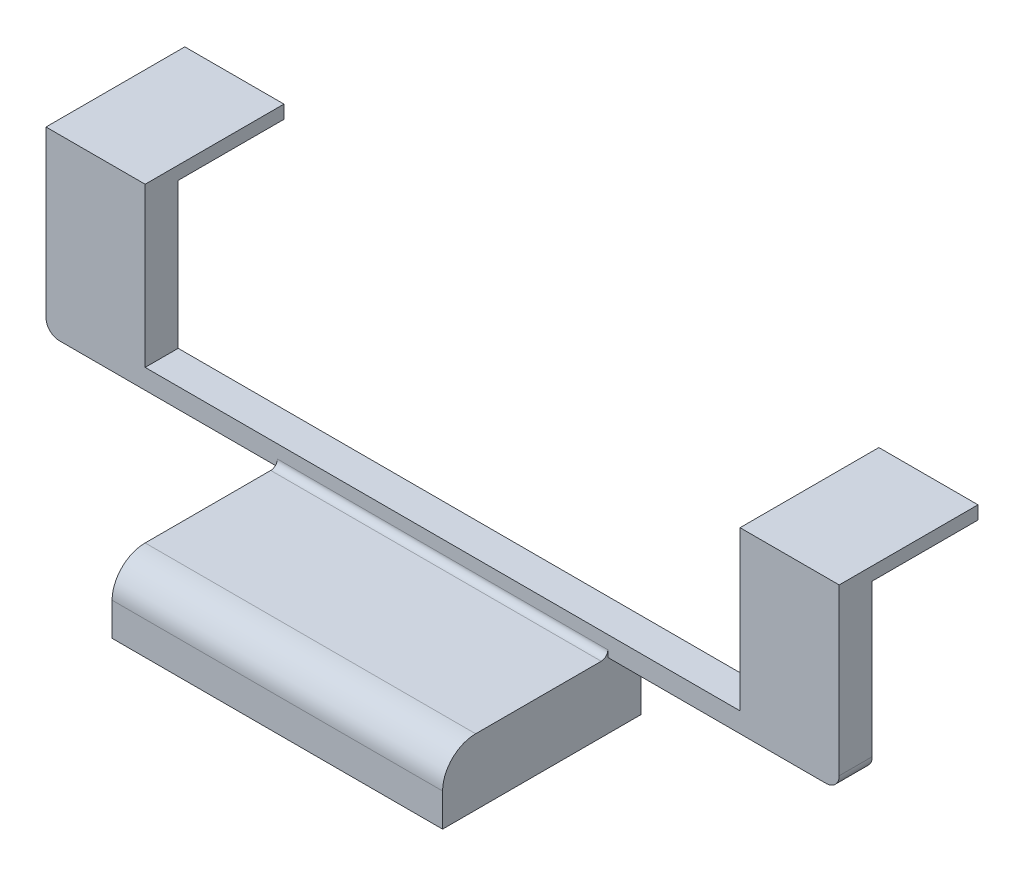
SolidWorks part; units mm, degrees
ref_plane "前视基准面" through (0, 0, 0) normal (0, 0, 1) x (1, 0, 0)
ref_plane "上视基准面" through (0, 0, 0) normal (0, 1, 0) x (1, 0, 0)
ref_plane "右视基准面" through (0, 0, 0) normal (1, 0, 0) x (0, 0, -1)
sketch "草图1" plane through (0, 0, 0) normal (0, 1, 0) x (1, 0, 0)
  line L0 (-55.774, -26.4776) -> (64.226, -26.4776)
  line L1 (64.226, -26.4776) -> (64.226, -31.4776)
  line L2 (64.226, -31.4776) -> (-55.774, -31.4776)
  line L3 (-55.774, -31.4776) -> (-55.774, -26.4776)
extrude "凸台-拉伸1" add sketch "草图1" along normal blind 3
sketch "草图2" plane through (0, 3, 0) normal (0, 1, 0) x (1, 0, 0)
  line L0 (-55.774, -26.4776) -> (-40.774, -26.4776)
  line L1 (64.226, -26.4776) -> (-55.774, -26.4776) construction
  line L2 (-40.774, -26.4776) -> (-40.774, -31.4776)
  line L3 (-55.774, -31.4776) -> (64.226, -31.4776) construction
  line L4 (-40.774, -31.4776) -> (-55.774, -31.4776)
  line L5 (-55.774, -31.4776) -> (-55.774, -26.4776)
  line L6 (64.226, -26.4776) -> (49.226, -26.4776)
  line L7 (49.226, -26.4776) -> (49.226, -31.4776)
  line L8 (49.226, -31.4776) -> (64.226, -31.4776)
  line L9 (64.226, -31.4776) -> (64.226, -26.4776)
extrude "凸台-拉伸2" add sketch "草图2" along normal blind 24
sketch "草图3" plane through (0, 0, 0) normal (0, -1, 0) x (1, 0, 0)
  line L0 (-20.774, 56.4776) -> (29.226, 56.4776)
  line L1 (29.226, 56.4776) -> (29.226, 26.4776)
  line L2 (29.226, 26.4776) -> (-20.774, 26.4776)
  line L3 (-20.774, 26.4776) -> (-20.774, 56.4776)
  line L5 (64.226, 26.4776) -> (-55.774, 26.4776) construction
  point P8 (4.226, 26.4776)
  point P11 (4.226, 26.4776)
extrude "凸台-拉伸3" add sketch "草图3" along normal blind 10
fillet "圆角6" radius 1 1 edges at (4.226, 0, 31.4776)
fillet "圆角7" radius 5 1 edges at (4.226, 0, 56.4776)
fillet "圆角9" radius 2 1 edges at (64.226, 0, 28.9776)
fillet "圆角10" radius 2 1 edges at (-55.774, 0, 28.9776)
sketch "草图4" plane through (0, -10, 0) normal (0, -1, 0) x (1, 0, 0)
  line L0 (29.226, 56.4776) -> (-20.774, 56.4776) construction
  line L1 (29.226, 26.4776) -> (29.226, 56.4776) construction
  arc A0 (-4.0934, 38.0444) -> (12.5455, 38.0444) centre (4.226, 41.4776) ccw
  arc A1 (12.5455, 38.0444) -> (12.5455, 44.9108) centre (13.226, 41.4776) ccw
  arc A2 (-4.0934, 44.9108) -> (-4.0934, 38.0444) centre (-4.774, 41.4776) ccw
  arc A3 (12.5455, 44.9108) -> (-4.0934, 44.9108) centre (4.226, 41.4776) ccw
  point P4 (4.226, 56.4776)
  point P8 (29.226, 41.4776)
extrude "切除-拉伸1" cut sketch "草图4" against normal blind 8
sketch "草图5" plane through (0, 0, 26.4776) normal (0, 0, -1) x (-1, 0, 0)
  line L0 (-64.226, 25) -> (-49.226, 25)
  line L1 (-49.226, 25) -> (-49.226, 27)
  line L2 (-49.226, 27) -> (-49.226, 3) construction
  line L3 (-49.226, 27) -> (-64.226, 27)
  line L4 (-64.226, 27) -> (-64.226, 2) construction
  line L5 (-64.226, 27) -> (-64.226, 25)
  line L6 (40.774, 25) -> (40.774, 27)
  line L7 (40.774, 27) -> (40.774, 3) construction
  line L8 (40.774, 27) -> (55.774, 27)
  line L9 (55.774, 27) -> (55.774, 2) construction
  line L10 (55.774, 27) -> (55.774, 25)
  line L11 (55.774, 25) -> (40.774, 25)
  point P2 (0, 0)
  point P12 (0, 0)
  point P19 (0, 0)
  point P20 (0, 0)
  point P21 (0, 0)
  point P22 (0, 0)
  point P23 (0, 0)
  point P24 (0, 0)
  point P26 (0, 0)
  point P27 (0, 0)
  point P28 (0, 0)
  point P29 (0, 0)
  point P30 (0, 0)
  point P31 (0, 0)
  point P35 (0, 0)
  point P36 (0, 0)
  point P37 (0, 0)
  point P38 (0, 0)
  point P39 (0, 0)
  point P40 (0, 0)
  point P41 (0, 0)
  point P42 (0, 0)
  point P43 (0, 0)
  point P44 (0, 0)
  point P46 (0, 0)
extrude "凸台-拉伸4" add sketch "草图5" along normal blind 16
